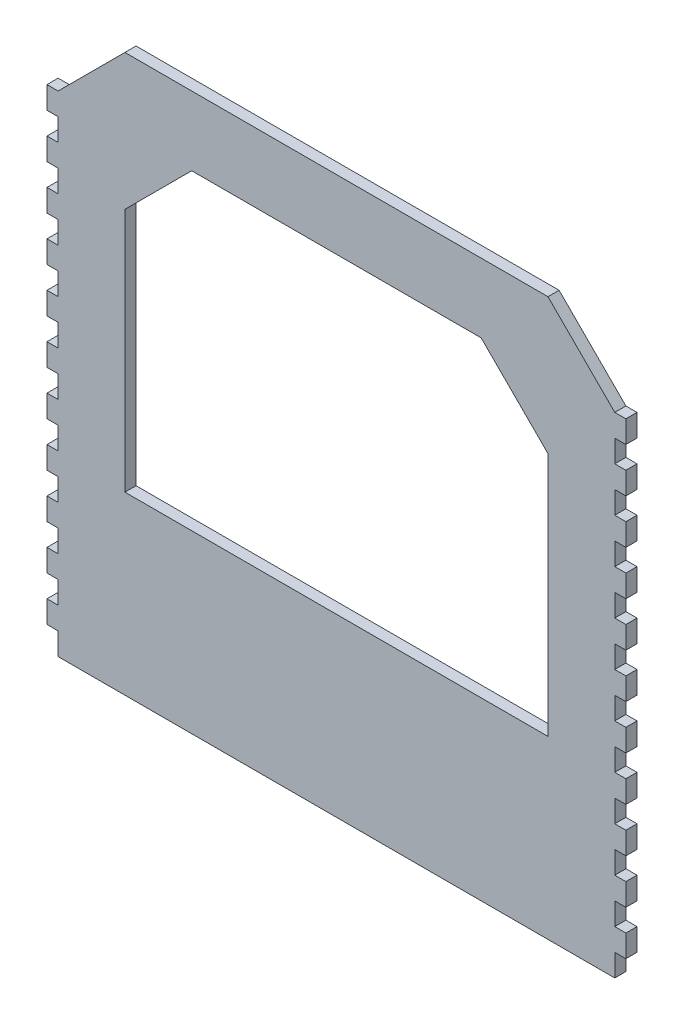
SolidWorks part; units mm, degrees
material "Buche"
ref_plane "Ebene vorne" through (0, 0, 0) normal (0, 0, 1) x (1, 0, 0)
ref_plane "Ebene oben" through (0, 0, 0) normal (0, 1, 0) x (1, 0, 0)
ref_plane "Ebene rechts" through (0, 0, 0) normal (1, 0, 0) x (0, 0, -1)
sketch "Skizze1" plane through (0, 0, 0) normal (0, 0, 1) x (1, 0, 0)
  line L196 (460.8962, 291.6639) -> (650.8962, 291.6639)
  line L197 (680.8962, 261.6639) -> (685.8962, 261.6639)
  line L198 (685.8962, 261.6639) -> (685.8962, 251.6639)
  line L199 (430.8962, 231.6639) -> (430.8962, 221.6639)
  line L200 (490.8962, 260.635) -> (620.8962, 260.635)
  line L201 (680.8962, 251.6639) -> (680.8962, 241.6639)
  line L202 (680.8962, 241.6639) -> (685.8962, 241.6639)
  line L203 (685.8962, 241.6639) -> (685.8962, 231.6639)
  line L204 (430.8962, 241.6639) -> (425.8962, 241.6639)
  line L205 (430.8962, 251.6639) -> (430.8962, 241.6639)
  line L206 (425.8962, 231.6639) -> (430.8962, 231.6639)
  line L207 (460.8962, 120.635) -> (460.8962, 230.635)
  line L208 (680.8962, 231.6639) -> (680.8962, 221.6639)
  line L209 (685.8962, 231.6639) -> (680.8962, 231.6639)
  line L210 (425.8962, 241.6639) -> (425.8962, 231.6639)
  line L211 (430.8962, 211.6639) -> (430.8962, 201.6639)
  line L212 (430.8962, 221.6639) -> (425.8962, 221.6639)
  line L213 (425.8962, 211.6639) -> (430.8962, 211.6639)
  line L214 (430.8962, 261.6639) -> (460.8962, 291.6639)
  line L215 (680.8962, 221.6639) -> (685.8962, 221.6639)
  line L216 (685.8962, 221.6639) -> (685.8962, 211.6639)
  line L217 (680.8962, 211.6639) -> (680.8962, 201.6639)
  line L218 (425.8962, 221.6639) -> (425.8962, 211.6639)
  line L219 (430.8962, 261.6639) -> (425.8962, 261.6639)
  line L220 (685.8962, 211.6639) -> (680.8962, 211.6639)
  line L221 (680.8962, 201.6639) -> (685.8962, 201.6639)
  line L222 (430.8962, 191.6639) -> (430.8962, 181.6639)
  line L223 (430.8962, 201.6639) -> (425.8962, 201.6639)
  line L224 (650.8962, 230.635) -> (620.8962, 260.635)
  line L225 (685.8962, 201.6639) -> (685.8962, 191.6639)
  line L226 (680.8962, 191.6639) -> (680.8962, 181.6639)
  line L227 (685.8962, 191.6639) -> (680.8962, 191.6639)
  line L228 (425.8962, 191.6639) -> (430.8962, 191.6639)
  line L229 (425.8962, 201.6639) -> (425.8962, 191.6639)
  line L230 (680.8962, 181.6639) -> (685.8962, 181.6639)
  line L231 (685.8962, 181.6639) -> (685.8962, 171.6639)
  line L232 (685.8962, 251.6639) -> (680.8962, 251.6639)
  line L233 (430.8962, 171.6639) -> (430.8962, 161.6639)
  line L234 (430.8962, 181.6639) -> (425.8962, 181.6639)
  line L235 (425.8962, 251.6639) -> (430.8962, 251.6639)
  line L236 (425.8962, 171.6639) -> (430.8962, 171.6639)
  line L237 (680.8962, 171.6639) -> (680.8962, 161.6639)
  line L238 (425.8962, 181.6639) -> (425.8962, 171.6639)
  line L239 (430.8962, 151.6639) -> (430.8962, 141.6639)
  line L240 (430.8962, 161.6639) -> (425.8962, 161.6639)
  line L241 (460.8962, 120.635) -> (650.8962, 120.635)
  line L242 (685.8962, 171.6639) -> (680.8962, 171.6639)
  line L243 (680.8962, 161.6639) -> (685.8962, 161.6639)
  line L244 (685.8962, 161.6639) -> (685.8962, 151.6639)
  line L245 (680.8962, 151.6639) -> (680.8962, 141.6639)
  line L246 (685.8962, 151.6639) -> (680.8962, 151.6639)
  line L247 (425.8962, 151.6639) -> (430.8962, 151.6639)
  line L248 (425.8962, 161.6639) -> (425.8962, 151.6639)
  line L249 (430.8962, 131.6639) -> (430.8962, 121.6639)
  line L250 (430.8962, 141.6639) -> (425.8962, 141.6639)
  line L251 (425.8962, 131.6639) -> (430.8962, 131.6639)
  line L252 (430.8962, 41.6639) -> (680.8962, 41.6639)
  line L253 (460.8962, 230.635) -> (490.8962, 260.635)
  line L254 (680.8962, 141.6639) -> (685.8962, 141.6639)
  line L255 (685.8962, 141.6639) -> (685.8962, 131.6639)
  line L256 (680.8962, 131.6639) -> (680.8962, 121.6639)
  line L257 (685.8962, 131.6639) -> (680.8962, 131.6639)
  line L258 (680.8962, 121.6639) -> (685.8962, 121.6639)
  line L259 (685.8962, 121.6639) -> (685.8962, 111.6639)
  line L260 (425.8962, 141.6639) -> (425.8962, 131.6639)
  line L261 (430.8962, 111.6639) -> (430.8962, 101.6639)
  line L262 (680.8962, 111.6639) -> (680.8962, 101.6639)
  line L263 (650.8962, 120.635) -> (650.8962, 230.635)
  line L264 (685.8962, 111.6639) -> (680.8962, 111.6639)
  line L265 (430.8962, 121.6639) -> (425.8962, 121.6639)
  line L266 (425.8962, 111.6639) -> (430.8962, 111.6639)
  line L267 (425.8962, 121.6639) -> (425.8962, 111.6639)
  line L268 (430.8962, 91.6639) -> (430.8962, 81.6639)
  line L269 (680.8962, 101.6639) -> (685.8962, 101.6639)
  line L270 (685.8962, 101.6639) -> (685.8962, 91.6639)
  line L271 (680.8962, 91.6639) -> (680.8962, 81.6639)
  line L272 (430.8962, 101.6639) -> (425.8962, 101.6639)
  line L273 (425.8962, 91.6639) -> (430.8962, 91.6639)
  line L274 (680.8962, 261.6639) -> (650.8962, 291.6639)
  line L275 (685.8962, 91.6639) -> (680.8962, 91.6639)
  line L276 (680.8962, 81.6639) -> (685.8962, 81.6639)
  line L277 (425.8962, 101.6639) -> (425.8962, 91.6639)
  line L278 (430.8962, 71.6639) -> (430.8962, 61.6639)
  line L279 (425.8962, 261.6639) -> (425.8962, 251.6639)
  line L280 (430.8962, 81.6639) -> (425.8962, 81.6639)
  line L281 (685.8962, 81.6639) -> (685.8962, 71.6639)
  line L282 (680.8962, 71.6639) -> (680.8962, 61.6639)
  line L283 (685.8962, 71.6639) -> (680.8962, 71.6639)
  line L284 (680.8962, 61.6639) -> (685.8962, 61.6639)
  line L285 (685.8962, 61.6639) -> (685.8962, 51.6639)
  line L286 (425.8962, 71.6639) -> (430.8962, 71.6639)
  line L287 (680.8962, 51.6639) -> (680.8962, 41.6639)
  line L288 (685.8962, 51.6639) -> (680.8962, 51.6639)
  line L289 (425.8962, 81.6639) -> (425.8962, 71.6639)
  line L290 (430.8962, 51.6639) -> (430.8962, 41.6639)
  line L291 (430.8962, 61.6639) -> (425.8962, 61.6639)
  line L292 (425.8962, 51.6639) -> (430.8962, 51.6639)
  line L293 (425.8962, 61.6639) -> (425.8962, 51.6639)
extrude "Aufsatz-Linear austragen2" add sketch "Skizze1" along normal blind 5
